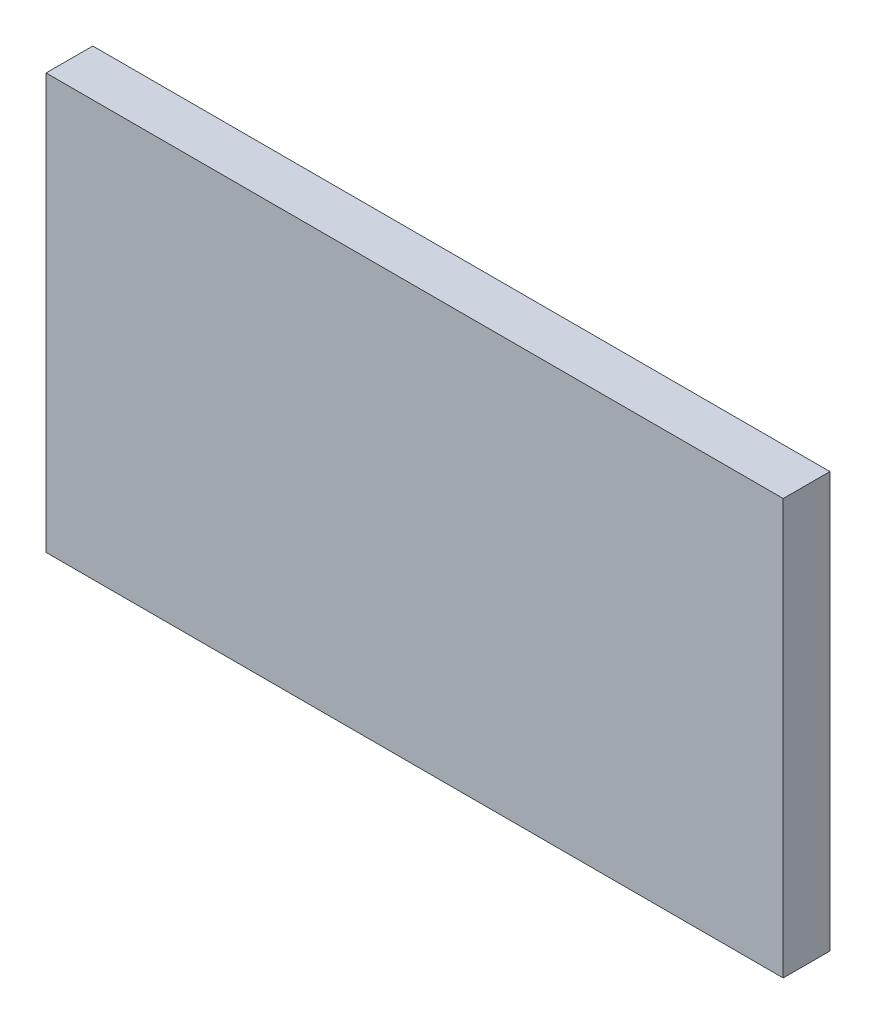
SolidWorks part; units mm, degrees
ref_plane "Front Plane" through (0, 0, 0) normal (0, 0, 1) x (1, 0, 0)
ref_plane "Top Plane" through (0, 0, 0) normal (0, 1, 0) x (1, 0, 0)
ref_plane "Right Plane" through (0, 0, 0) normal (1, 0, 0) x (0, 0, -1)
sketch "Sketch1" plane through (0, 0, 0) normal (0, 0, 1) x (1, 0, 0)
  line L1 (0, 0) -> (76.2, 0)
  line L2 (0, 0) -> (0, 42.926)
  line L3 (0, 42.926) -> (76.2, 42.926)
  line L4 (76.2, 0) -> (76.2, 42.926)
  dimension "D1" = 76.2
  dimension "D2" = 42.926
extrude "Boss-Extrude1" add sketch "Sketch1" along normal blind 4.826
equation "\"MDF\"= 0.19in"
equation "\"PVCID\" = 2.067in"
equation "\"PVCOD\" = 2.375in"
equation "\"GenDiameter\"= 60mm"
equation "\"GenCutDiameter\" = 1.8in"
equation "\"GenCutDistance\" = 1"
equation "\"TowerHeight\" = 6in"
equation "\"TowerFrontBase\" = 3in"
equation "\"FunnelHeight\" = 1in"
equation "\"FunnelAngle\" = 20"
equation "\"TowerSideBase\" = 3in"
equation "\"TowerPanelLength\" = 2in"
equation "\"TowerPanelLeeway\" = 0.5in"
equation "\"BaseLength\" = 9in"
equation "\"BaseWidth\" = 10in"
equation "\"WheelHoleLength\" = 3.25in"
equation "\"WheelHoleWidth\" = 26mm"
equation "\"WheelHoleFromBack\" = 1.5in"
equation "\"DropLength\" = 1in"
equation "\"DropWidth\" = 8.5in"
equation "\"BumperWidth\" = 2in"
equation "\"SmallHexDiameter\" = 0.185in"
equation "\"SmallHexHeight\" = 0.701in"
equation "\"ScrewSize\" = 0.106in"
equation "\"BigHexDiameter\" = 0.251in"
equation "\"BigHexHeight\" = 0.374in"
equation "\"PCBThickness\" = 0.066in"
equation "\"ConnectorHeight\" = 0.517in"
equation "\"BoardHeight\" = 0.583in"
equation "\"UnoStackHeight\" = 1.351in"
equation "\"UnoStackWidth\" = 3.053in"
equation "\"UnoStackLength\" = 3.152in"
equation "\"HBridgeWidth\" = 1.797in"
equation "\"HBridgeLength\" = 2.236in"
equation "\"DSWidth\" = 1.820in"
equation "\"DSLength\" = 1.833in"
equation "\"StepperWidth\" = 1.799in"
equation "\"StepperLength\" = 2.248in"
equation "\"ULNWidth\" = 1.304in"
equation "\"ULNLength\" = 1.545in"
equation "\"VSwitchHeight\" = 0.392in"
equation "\"VSwitchWidth\" = 0.637in"
equation "\"VSwitchLength\" = 1.097in"
equation "\"SkateWheelDiameter\" = 80mm"
equation "\"SkateWheelThickness\" = 24mm"
equation "\"BaseDistance\" = 3in"
equation "\"DummyVar\" = 2in"
equation "\"D2@Sketch1\"=\"MDF\"+1.5in"
equation "\"D1@Boss-Extrude1\"=\"MDF\""
